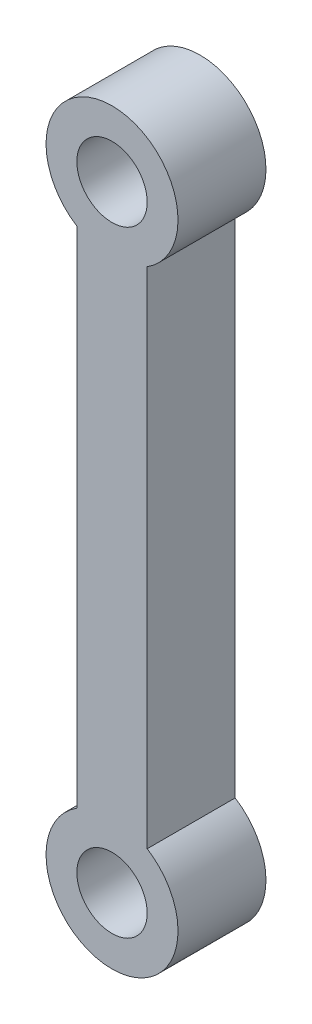
SolidWorks part; units mm, degrees
ref_plane "Plano frontal" through (0, 0, 0) normal (0, 0, 1) x (1, 0, 0)
ref_plane "Plano superior" through (0, 0, 0) normal (0, 1, 0) x (1, 0, 0)
ref_plane "Plano direito" through (0, 0, 0) normal (1, 0, 0) x (0, 0, -1)
sketch "Esboço1" plane through (0, 0, 0) normal (0, 0, 1) x (1, 0, 0)
  line L0 (4, 63.6557) -> (4, 6.3443)
  line L1 (0, 70) -> (0, 0) construction
  line L2 (-4, 63.6557) -> (-4, 6.3443)
  circle A0 centre (0, 70) radius 4
  circle A1 centre (0, 0) radius 4
  arc A2 (4, 63.6557) -> (-4, 63.6557) centre (0, 70) ccw
  arc A3 (-4, 6.3443) -> (4, 6.3443) centre (0, 0) ccw
  dimension "D1" = 8
  dimension "D2" = 15
  dimension "D3" = 70
  dimension "D4" = 8
extrude "Ressalto-extrusão1" add sketch "Esboço1" along normal blind 10 contours L0 A3 L2 A2
